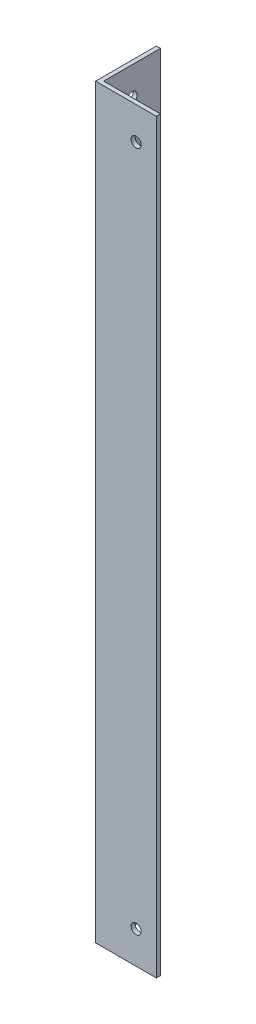
SolidWorks part; units mm, degrees
ref_plane "正面" through (0, 0, 0) normal (0, 0, 1) x (1, 0, 0)
ref_plane "平面" through (0, 0, 0) normal (0, 1, 0) x (1, 0, 0)
ref_plane "右側面" through (0, 0, 0) normal (1, 0, 0) x (0, 0, -1)
sketch "ｽｹｯﾁ1" plane through (0, 0, 0) normal (0, 1, 0) x (1, 0, 0)
  line L1 (0, 0) -> (15, 0)
  line L2 (0, 0) -> (0, -1)
  line L3 (0, -1) -> (15, -1)
  line L4 (15, 0) -> (15, -1)
  dimension "D1" = 15
  dimension "D2" = 1
sketch "ｽｹｯﾁ2" plane through (0, 0, 0) normal (0, 1, 0) x (1, 0, 0)
extrude "ﾎﾞｽ - 押し出し1" add sketch "ｽｹｯﾁ1" along normal blind 184
sketch "ｽｹｯﾁ3" plane through (0, 0, 0) normal (0, 0, -1) x (-1, 0, 0)
  line L1 (0, 184) -> (-1, 184)
  line L2 (0, 184) -> (0, 0)
  line L3 (0, 0) -> (-1, 0)
  line L4 (-1, 184) -> (-1, 0)
  dimension "D1" = 1
  dimension "D2" = 184
extrude "ﾎﾞｽ - 押し出し2" add sketch "ｽｹｯﾁ3" along normal blind 14
hole_wizard "M3x0.5 ねじ穴1" positions "ｽｹｯﾁ4" profile "ｽｹｯﾁ5" tap size "M3x0.5" standard "JIS" end condition through all
sketch "ｽｹｯﾁ4" plane through (0, 0, 0) normal (-1, 0, 0) x (0, 0, 1)
  line L0 (-14, 184) -> (1, 184) construction
  line L1 (-14, 0) -> (-14, 184) construction
  line L2 (8.25, 0) -> (-8.25, 0) construction
  point P0 (-7, 7)
  point P2 (-7, 177)
  dimension "D1" = 7
  dimension "D2" = 7
  dimension "D3" = 7
  dimension "D4" = 7
sketch "ｽｹｯﾁ5" plane through (0, 7, -7) normal (0, 1, 0) x (0, 0, 1)
  line L0 (0, 0) -> (0, 15)
  line L1 (0, 15) -> (1.25, 15)
  line L2 (1.25, 15) -> (1.25, 0)
  line L5 (1.25, 0) -> (0, 0)
  line L11 (0, -6.35) -> (0, 107.95) construction
  dimension "次ｻｰﾌｪｽまでのねじ下穴ﾄﾞﾘﾙ直径" = 2.5
  dimension "次ｻｰﾌｪｽまでのねじ下穴ﾄﾞﾘﾙの深さ" = 15
cosmetic thread "穴のねじ山1" parameters "D2"=3
cosmetic thread "穴のねじ山2" parameters "D2"=3
hole_wizard "M3x0.5 ねじ穴2" positions "ｽｹｯﾁ6" profile "ｽｹｯﾁ7" tap size "M3x0.5" standard "JIS" end condition through all
sketch "ｽｹｯﾁ6" plane through (0, 0, 1) normal (0, 0, 1) x (1, 0, 0)
  line L0 (15, 184) -> (15, 0) construction
  line L1 (8.25, 0) -> (-8.25, 0) construction
  line L2 (0, 184) -> (15, 184) construction
  point P0 (10, 8)
  point P2 (10, 176)
  dimension "D1" = 5
  dimension "D2" = 8
  dimension "D3" = 8
  dimension "D4" = 5
sketch "ｽｹｯﾁ7" plane through (10, 8, 1) normal (1, 0, 0) x (0, -1, 0)
  line L0 (0, 0) -> (0, 15)
  line L1 (0, 15) -> (1.25, 15)
  line L2 (1.25, 15) -> (1.25, 0)
  line L5 (1.25, 0) -> (0, 0)
  line L11 (0, -6.35) -> (0, 107.95) construction
  dimension "次ｻｰﾌｪｽまでのねじ下穴ﾄﾞﾘﾙ直径" = 2.5
  dimension "次ｻｰﾌｪｽまでのねじ下穴ﾄﾞﾘﾙの深さ" = 15
cosmetic thread "穴のねじ山3" parameters "D2"=3
cosmetic thread "穴のねじ山4" parameters "D2"=3
